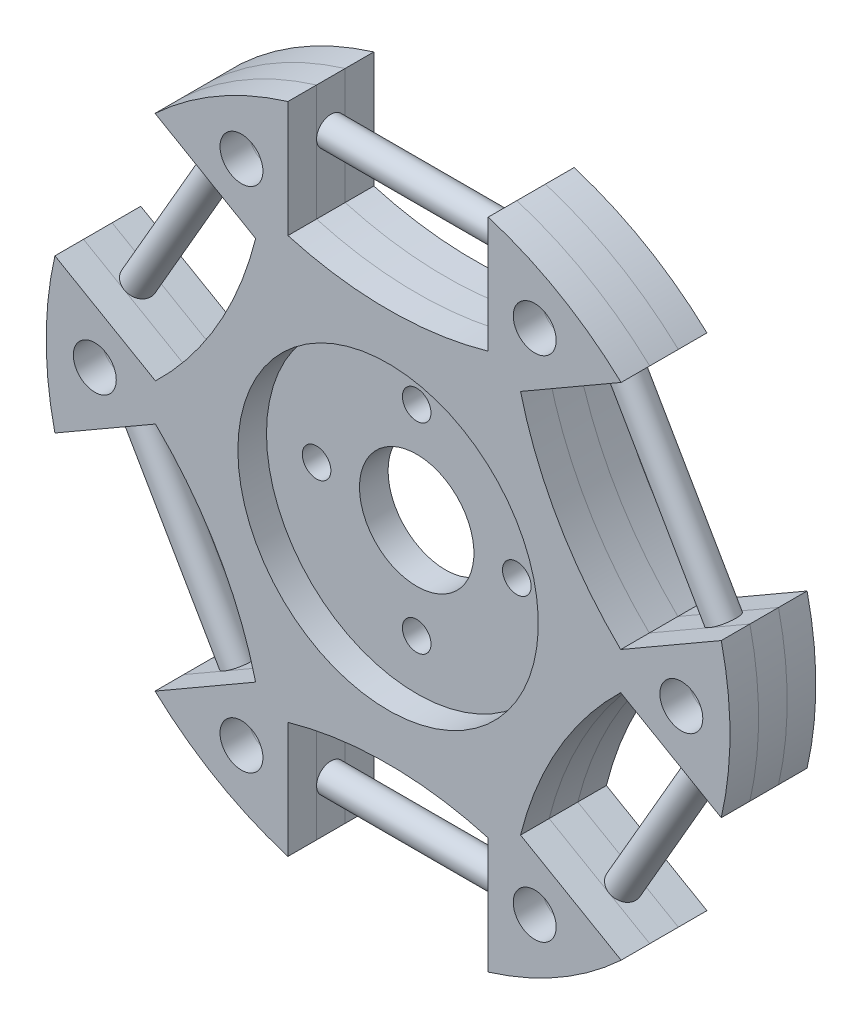
SolidWorks part; units mm, degrees
material "Thornel Mat VMA"
ref_plane "前视基准面" through (0, 0, 0) normal (0, 0, 1) x (1, 0, 0)
ref_plane "上视基准面" through (0, 0, 0) normal (0, 1, 0) x (1, 0, 0)
ref_plane "右视基准面" through (0, 0, 0) normal (1, 0, 0) x (0, 0, -1)
sketch "草图1" plane through (0, 0, 0) normal (0, 0, 1) x (1, 0, 0)
  circle A0 centre (0, 0) radius 25.4
  circle A1 centre (0, 0) radius 10.5
  dimension "D1" = 50.8
  dimension "D2" = 21
extrude "凸台-拉伸1" add sketch "草图1" along normal blind 2
sketch "草图2" plane through (0, 0, 2) normal (0, 0, 1) x (1, 0, 0)
  circle A0 centre (0, 0) radius 25.4
  circle A1 centre (0, 0) radius 4
  dimension "D1" = 8
extrude "凸台-拉伸2" add sketch "草图2" along normal blind 2 separate body
sketch "草图3" plane through (0, 0, 4) normal (0, 0, 1) x (1, 0, 0)
  circle A0 centre (0, 0) radius 25.4
  circle A1 centre (0, 0) radius 10.5
  dimension "D1" = 21
extrude "凸台-拉伸3" add sketch "草图3" along normal blind 2 separate body
sketch "草图4" plane through (0, 0, 6) normal (0, 0, 1) x (1, 0, 0)
  line L0 (9.2597, 13.429) -> (17.6452, 18.2704)
  line L1 (7, 14.7336) -> (7, 24.4164)
  line L2 (-7, 14.7336) -> (-7, 24.4164)
  line L3 (16.2597, 1.3046) -> (24.6452, 6.146)
  line L4 (16.2597, -1.3046) -> (24.6452, -6.146)
  line L5 (9.2597, -13.429) -> (17.6452, -18.2704)
  line L6 (7, -14.7336) -> (7, -24.4164)
  line L7 (-7, -14.7336) -> (-7, -24.4164)
  line L8 (-9.2597, -13.429) -> (-17.6452, -18.2704)
  line L9 (-16.2597, -1.3046) -> (-24.6452, -6.146)
  line L10 (-16.2597, 1.3046) -> (-24.6452, 6.146)
  line L11 (-9.2597, 13.429) -> (-17.6452, 18.2704)
  arc A0 (7, 24.4164) -> (-7, 24.4164) centre (0, 0) ccw
  arc A1 (9.2597, 13.429) -> (16.2597, 1.3046) centre (33.9049, 19.575) ccw
  arc A2 (-7, 14.7336) -> (7, 14.7336) centre (0, 39.15) ccw
  arc A3 (24.6452, 6.146) -> (17.6452, 18.2704) centre (0, 0) ccw
  arc A4 (16.2597, -1.3046) -> (9.2597, -13.429) centre (33.9049, -19.575) ccw
  arc A5 (17.6452, -18.2704) -> (24.6452, -6.146) centre (0, 0) ccw
  arc A6 (7, -14.7336) -> (-7, -14.7336) centre (0, -39.15) ccw
  arc A7 (-7, -24.4164) -> (7, -24.4164) centre (0, 0) ccw
  arc A8 (-9.2597, -13.429) -> (-16.2597, -1.3046) centre (-33.9049, -19.575) ccw
  arc A9 (-24.6452, -6.146) -> (-17.6452, -18.2704) centre (0, 0) ccw
  arc A10 (-16.2597, 1.3046) -> (-9.2597, 13.429) centre (-33.9049, 19.575) ccw
  arc A11 (-17.6452, 18.2704) -> (-24.6452, 6.146) centre (0, 0) ccw
  point P34 (0, 0)
  dimension "D1" = 50.8
  dimension "D2" = 6
  dimension "D3" = 50.8
extrude "切除-拉伸1" cut sketch "草图4" against normal blind 20.5
sketch "草图5" plane through (0, 0, 6) normal (0, 0, 1) x (1, 0, 0)
  circle A0 centre (0, 0) radius 4 construction
  circle A2 centre (10.25, 17.7535) radius 1.5
  circle A3 centre (20.5, 0) radius 1.5
  circle A4 centre (10.25, -17.7535) radius 1.5
  circle A5 centre (-10.25, -17.7535) radius 1.5
  circle A6 centre (-20.5, 0) radius 1.5
  circle A7 centre (-10.25, 17.7535) radius 1.5
  point P21 (0, 0)
  dimension "D1" = 20.5
  dimension "D2" = 3
  dimension "D3" = 6
extrude "切除-拉伸2" cut sketch "草图5" against normal blind 20.5
sketch "草图6" plane through (-7, 0, 0) normal (1, 0, 0) x (0, 0, -1)
  line L0 (-2, 24.4164) -> (-2, 14.7336) construction
  circle A0 centre (-3, 19.575) radius 1
  dimension "D1" = 2
  dimension "D2" = 1
extrude "凸台-拉伸4" add sketch "草图6" along normal blind 14
pattern_circular "阵列(圆周)1" count 6 over 360 about axis through (0, 0, 6) along (0, 0, 1) of "凸台-拉伸4"
sketch "草图7" plane through (0, 0, 4) normal (0, 0, 1) x (1, 0, 0)
  circle A1 centre (0, 7) radius 1
  circle A2 centre (7, 0) radius 1
  circle A3 centre (0, -7) radius 1
  circle A4 centre (-7, 0) radius 1
  point P14 (0, 0)
  dimension "D2" = 2
  dimension "D3" = 4
extrude "切除-拉伸3" cut sketch "草图7" against normal blind 14
sketch "草图8" plane through (0, 0, 6) normal (0, 0, 1) x (1, 0, 0)
  circle A0 centre (0, 0) radius 23.9
  dimension "D1" = 47.8
extrude "切除-拉伸-薄壁1" cut sketch "草图8" against normal blind 10 thin
